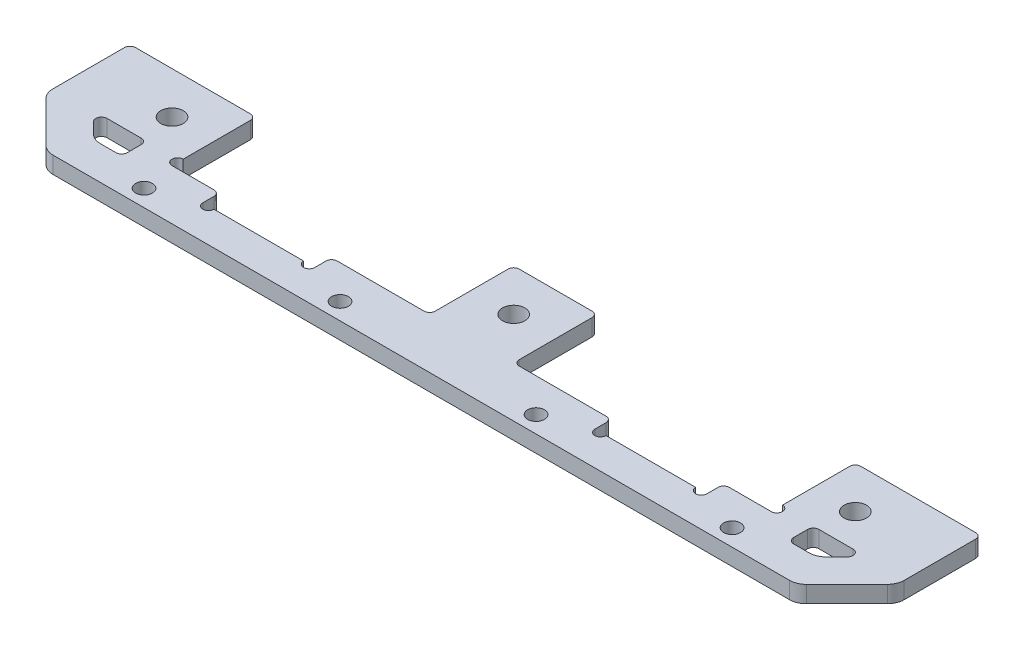
SolidWorks part; units mm, degrees
material "Thornel Mat VMA"
ref_plane "前视基准面" through (0, 0, 0) normal (0, 0, 1) x (1, 0, 0)
ref_plane "上视基准面" through (0, 0, 0) normal (0, 1, 0) x (1, 0, 0)
ref_plane "右视基准面" through (0, 0, 0) normal (1, 0, 0) x (0, 0, -1)
sketch "草图1" plane through (0, 0, 0) normal (0, 1, 0) x (1, 0, 0)
  line L0 (-53.5, 24) -> (-53.5, 9)
  line L1 (-76, 24) -> (-53.5, 24)
  line L2 (-76, 24) -> (-76, 9)
  line L4 (76, 24) -> (76, 9)
  line L5 (-53.5, 9) -> (-7.5, 9)
  line L6 (-7.5, 9) -> (-7.5, 24)
  line L7 (-7.5, 24) -> (7.5, 24)
  line L8 (-52.5, 3) -> (-17.5, 3) construction
  line L9 (0, 0) -> (0, 24) construction
  line L10 (-61, 16.5) -> (0, 16.5) construction
  line L11 (-67, 0) -> (67, 0)
  line L12 (-67, 0) -> (-76, 9)
  line L13 (0, -55) -> (0, 55) construction
  line L14 (-17.5, 3) -> (17.5, 3) construction
  line L15 (67, 0) -> (76, 9)
  line L16 (53.5, 9) -> (7.5, 9)
  line L17 (76, 24) -> (53.5, 24)
  line L18 (53.5, 24) -> (53.5, 9)
  line L19 (7.5, 9) -> (7.5, 24)
  circle A0 centre (-61, 16.5) radius 2
  circle A1 centre (-52.5, 3) radius 1.5
  circle A2 centre (-17.5, 3) radius 1.5
  circle A3 centre (0, 16.5) radius 2
  circle A6 centre (17.5, 3) radius 1.5
  circle A7 centre (52.5, 3) radius 1.5
  circle A8 centre (61, 16.5) radius 2
  circle A9 centre (-17.5, 3) radius 6 construction
  dimension "D2" = 15
  dimension "D3" = 4
  dimension "D5" = 7.5
  dimension "D9" = 3
  dimension "D11" = 35
  dimension "D13" = 12
  dimension "D1" = 152
  dimension "D4" = 22.5
  dimension "D6" = 15
  dimension "D7" = 6
  dimension "D8" = 15
  dimension "D10" = 3
  dimension "D12" = 135
extrude "凸台-拉伸1" add sketch "草图1" along normal blind 3
sketch "草图2" plane through (0, 3, 0) normal (0, 1, 0) x (1, 0, 0)
  line L0 (0, -1.65) -> (0, 1.65) construction
  line L1 (45, 6) -> (25, 6)
  line L2 (45, 6) -> (45, 9)
  line L3 (25, 6) -> (25, 9)
  line L4 (25, 9) -> (45, 9)
  line L6 (-25, 6) -> (-25, 9)
  line L7 (-45, 6) -> (-45, 9)
  line L8 (-7.5, 9) -> (-53.5, 9) construction
  line L9 (-25, 9) -> (-45, 9)
  line L10 (-69.0147, 10.5) -> (-59.5, 10.5)
  line L11 (-45, 6) -> (-25, 6)
  line L12 (-59.5, 10.5) -> (-59.5, 6)
  line L13 (-64.5147, 6) -> (-69.0147, 10.5)
  line L14 (-53.5, 9) -> (-53.5, 24) construction
  line L15 (-76, 9) -> (-67, 0) construction
  line L17 (-64.5147, 6) -> (-59.5, 6)
  line L22 (-67, 0) -> (67, 0) construction
  line L23 (64.5147, 6) -> (59.5, 6)
  line L24 (64.5147, 6) -> (69.0147, 10.5)
  line L25 (59.5, 10.5) -> (59.5, 6)
  line L26 (69.0147, 10.5) -> (59.5, 10.5)
  circle A0 centre (-52.5, 3) radius 1.5 construction
  circle A1 centre (-61, 16.5) radius 2 construction
  dimension "D3" = 7.5
  dimension "D1" = 3
  dimension "D2" = 20
  dimension "D4" = 6
  dimension "D5" = 6
  dimension "D6" = 6
  dimension "D7" = 6
extrude "切除-拉伸1" cut sketch "草图2" against normal through all
sketch "草图3" plane through (0, 3, 0) normal (0, 1, 0) x (1, 0, 0)
  line L0 (-53.5, 9) -> (-53.5, 24) construction
  line L2 (-45, 6) -> (-25, 6) construction
  line L3 (0, -1.65) -> (0, 1.65) construction
  circle A0 centre (-53.5, 10) radius 1
  circle A2 centre (-44, 6) radius 1
  circle A3 centre (-26, 6) radius 1
  circle A4 centre (26, 6) radius 1
  circle A5 centre (44, 6) radius 1
  circle A7 centre (53.5, 10) radius 1
  dimension "D1" = 2
extrude "切除-拉伸2" cut sketch "草图3" against normal through all
fillet "圆角1" radius 1 18 edges at (76, 1.5, -24) (53.5, 1.5, -24) (7.5, 1.5, -24) (-7.5, 1.5, -24) (-76, 1.5, -24) (-53.5, 1.5, -24) (59.5, 1.5, -6) (69.0147, 1.5, -10.5) (59.5, 1.5, -10.5) (-69.0147, 1.5, -10.5) (-59.5, 1.5, -6) (-59.5, 1.5, -10.5) (45, 1.5, -9) (25, 1.5, -9) (-25, 1.5, -9) (-45, 1.5, -9) (7.5, 1.5, -9) (-7.5, 1.5, -9)
fillet "圆角2" radius 3 6 edges at (76, 1.5, -9) (67, 1.5, 0) (-67, 1.5, 0) (-76, 1.5, -9) (-64.5147, 1.5, -6) (64.5147, 1.5, -6)
